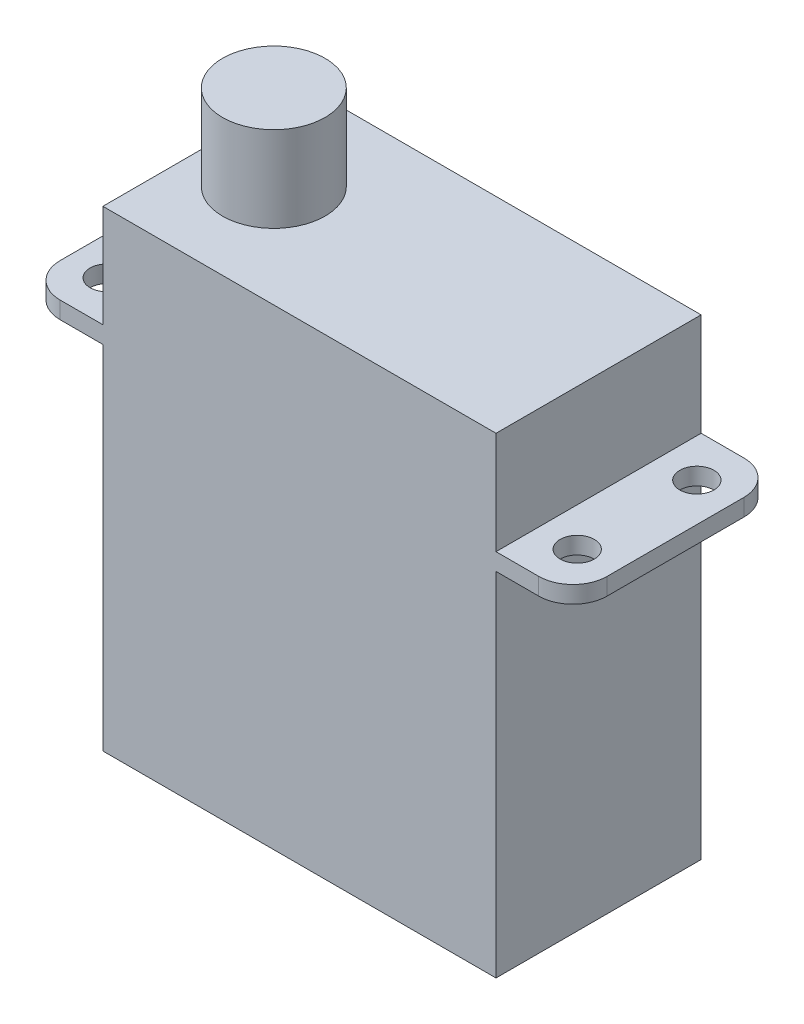
SolidWorks part; units mm, degrees
ref_plane "Front Plane" through (0, 0, 0) normal (0, 0, 1) x (1, 0, 0)
ref_plane "Top Plane" through (0, 0, 0) normal (0, 1, 0) x (1, 0, 0)
ref_plane "Right Plane" through (0, 0, 0) normal (1, 0, 0) x (0, 0, -1)
sketch "Эскиз1" plane through (0, 0, 0) normal (0, 0, 1) x (1, 0, 0)
  line L0 (0, 5.0732) -> (0, -2.902) construction
  line L1 (-11.5, -13.8) -> (11.5, -13.8)
  line L2 (-11.5, -13.8) -> (-11.5, 13.8)
  line L3 (-11.5, 13.8) -> (11.5, 13.8)
  line L4 (11.5, -13.8) -> (11.5, 13.8)
  line L5 (-11.5, -13.8) -> (11.5, 13.8) construction
  line L6 (-11.5, 13.8) -> (11.5, -13.8) construction
  line L7 (-16, 6.8) -> (-11.5, 6.8)
  line L8 (-16, 6.8) -> (-16, 7.8)
  line L9 (-16, 7.8) -> (-11.5, 7.8)
  line L10 (-11.5, 6.8) -> (-11.5, 7.8)
  line L11 (-16, 6.8) -> (-11.5, 7.8) construction
  line L12 (-16, 7.8) -> (-11.5, 6.8) construction
  line L13 (16, 7.8) -> (11.5, 7.8)
  line L14 (11.5, 6.8) -> (11.5, 7.8)
  line L15 (16, 6.8) -> (11.5, 6.8)
  line L16 (16, 6.8) -> (16, 7.8)
  point P0 (0, 0)
  point P5 (-13.75, 7.3)
  dimension "D1" = 23
  dimension "D2" = 27.6
  dimension "D3" = 20.6
  dimension "D4" = 1
  dimension "D5" = 32
extrude "Бобышка-Вытянуть1" add sketch "Эскиз1" along normal mid plane 12 contours L1 L4 L3 L2 | L9 L8 L7 L2 | L15 L16 L13 L4
sketch "Эскиз2" plane through (0, 13.8, 0) normal (0, 1, 0) x (1, 0, 0)
  line L0 (-11.5, 0) -> (11.5, 0) construction
  line L1 (-11.5, -6) -> (-11.5, 6) construction
  line L2 (11.5, -6) -> (11.5, 6) construction
  circle A0 centre (-7.5, 0) radius 3
  dimension "D1" = 6
  dimension "D2" = 4
extrude "Бобышка-Вытянуть2" add sketch "Эскиз2" along normal blind 5
sketch "Эскиз3" plane through (0, 7.8, 0) normal (0, 1, 0) x (1, 0, 0)
  line L0 (-13.75, 6) -> (-13.75, -6) construction
  line L1 (-16, 6) -> (-11.5, 6) construction
  line L2 (-16, -6) -> (-11.5, -6) construction
  line L3 (0, -6) -> (0, 6) construction
  line L4 (-11.5, -6) -> (11.5, -6) construction
  line L5 (-11.5, 6) -> (11.5, 6) construction
  circle A0 centre (-13.75, 3.5) radius 1
  circle A1 centre (-13.75, -3.5) radius 1
  circle A2 centre (13.75, -3.5) radius 1
  circle A3 centre (13.75, 3.5) radius 1
  dimension "D1" = 2
  dimension "D2" = 7
  dimension "D3" = 2.5
extrude "Вырез-Вытянуть1" cut sketch "Эскиз3" against normal through all both and the other way through all
fillet "Скругление1" radius 2 4 edges at (-16, 7.3, -6) (16, 7.3, -6) (16, 7.3, 6) (-16, 7.3, 6)
